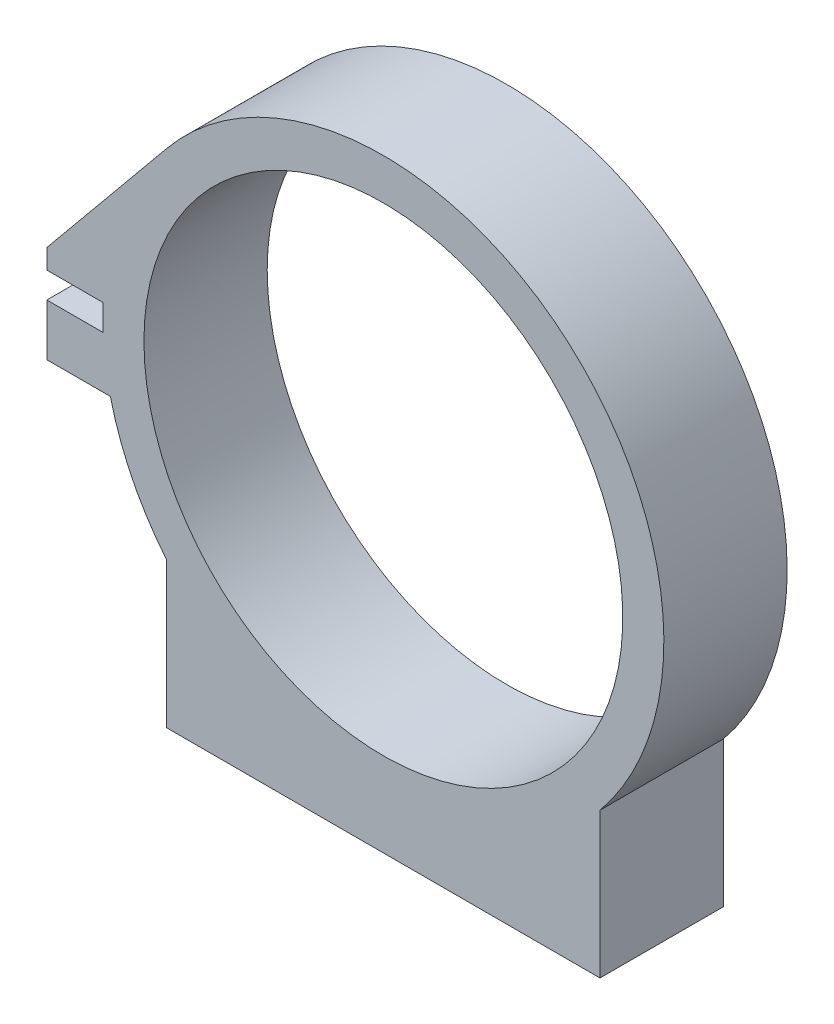
SolidWorks part; units mm, degrees
ref_plane "Front Plane" through (0, 0, 0) normal (0, 0, 1) x (1, 0, 0)
ref_plane "Top Plane" through (0, 0, 0) normal (0, 1, 0) x (1, 0, 0)
ref_plane "Right Plane" through (0, 0, 0) normal (1, 0, 0) x (0, 0, -1)
sketch "Sketch1" plane through (0, 0, 0) normal (0, 0, 1) x (1, 0, 0)
  line L0 (-16.7386, 13.7704) -> (-26, 2.5128)
  line L1 (-26, 2.5128) -> (-26, 1)
  line L2 (-26, 1) -> (-21.6519, 1)
  line L3 (-26, -1) -> (-21.6519, -1)
  line L4 (-26, -1) -> (-26, -5)
  line L5 (-26, -5) -> (-21.0904, -5)
  line L6 (-16.7386, -13.7704) -> (-16.7386, -25)
  line L7 (-16.7386, -25) -> (16.7386, -25)
  line L8 (16.7386, -25) -> (16.7386, -13.7704)
  line L9 (0, -25) -> (0, 0) construction
  line L10 (-21.675, 0) -> (0, 0) construction
  circle A0 centre (0, 0) radius 18.5
  arc A1 (16.7386, -13.7704) -> (-16.7386, 13.7704) centre (0, 0) ccw
  arc A2 (-21.0904, -5) -> (-16.7386, -13.7704) centre (0, 0) ccw
  arc A3 (-21.6519, 1) -> (-21.6519, -1) centre (0, 0) ccw
  point P9 (0, 0)
  point P17 (-26, 0.9877)
  dimension "D2" = 37
  dimension "D3" = 3.175
  dimension "D1" = 33.4772
  dimension "D4" = 26
  dimension "D5" = 25
  dimension "D6" = 2
  dimension "D7" = 4
extrude "Boss-Extrude1" add sketch "Sketch1" along normal blind 9.525
sketch "Sketch2" plane through (0, -25, 0) normal (0, -1, 0) x (1, 0, 0)
  line L0 (-16.7386, 4.7625) -> (-13.4747, 4.7625) construction
  line L1 (-16.7386, 9.525) -> (-16.7386, 0) construction
  line L2 (-13.4747, 4.7625) -> (13.4747, 4.7625) construction
  line L3 (13.4747, 4.7625) -> (16.7386, 4.7625) construction
  line L4 (16.7386, 9.525) -> (16.7386, 0) construction
  circle A0 centre (-13.4747, 4.7625) radius 1.3891
  circle A1 centre (13.4747, 4.7625) radius 1.3891
  dimension "D2" = 2.7781
  dimension "D1" = 26.9494
extrude "Cut-Extrude1" cut sketch "Sketch2" against normal blind 6.35
sketch "Sketch3" plane through (0, -5, 0) normal (0, -1, 0) x (1, 0, 0)
  line L0 (-26, 9.525) -> (-21.0904, 9.525) construction
  line L1 (-23.5452, 4.7625) -> (-26, 4.7625) construction
  line L2 (-23.5452, 4.7625) -> (-23.5452, 9.525) construction
  line L3 (-23.5452, 9.525) -> (-26, 9.525) construction
  line L4 (-26, 4.7625) -> (-26, 9.525) construction
  line L5 (-26, 9.525) -> (-26, 0) construction
  circle A0 centre (-23.5452, 4.7625) radius 1.3891
  point P6 (-23.5452, 9.525)
  point P9 (-26, 4.7625)
  dimension "D1" = 2.7781
extrude "Cut-Extrude2" cut sketch "Sketch3" against normal up to surface (10.4967 mm away)
